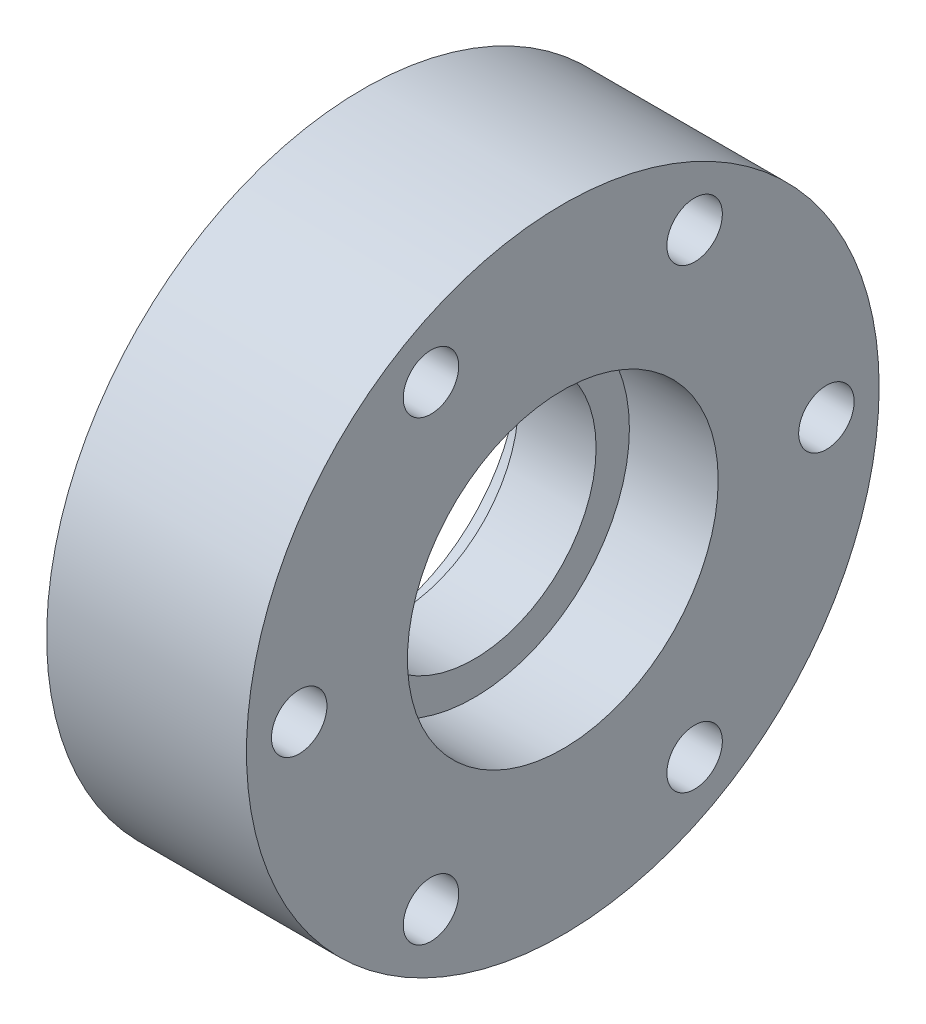
SolidWorks part; units mm, degrees
ref_plane "Front Plane" through (0, 0, 0) normal (0, 0, 1) x (1, 0, 0)
ref_plane "Top Plane" through (0, 0, 0) normal (0, 1, 0) x (1, 0, 0)
ref_plane "Right Plane" through (0, 0, 0) normal (1, 0, 0) x (0, 0, -1)
sketch "Sketch1" plane through (0, 0, 0) normal (1, 0, 0) x (0, 0, -1)
  line L0 (-23.75, 0) -> (0, 0) construction
  circle A0 centre (0, 0) radius 28.5
  circle A1 centre (0, 0) radius 11
  circle A2 centre (-23.75, 0) radius 2.5
  circle A3 centre (-11.875, 20.5681) radius 2.5
  circle A4 centre (11.875, 20.5681) radius 2.5
  circle A5 centre (23.75, 0) radius 2.5
  circle A6 centre (11.875, -20.5681) radius 2.5
  circle A7 centre (-11.875, -20.5681) radius 2.5
  point P18 (0, 0)
  dimension "D2" = 5
  dimension "D3" = 57
  dimension "D4" = 22
  dimension "D1" = 23.75
  dimension "D5" = 6
extrude "Boss-Extrude1" add sketch "Sketch1" along normal blind 18
sketch "Sketch2" plane through (18, 0, 0) normal (1, 0, 0) x (0, 0, -1)
  circle A1 centre (0, 0) radius 14
  circle A2 centre (0, 0) radius 11 construction
  circle A3 centre (0, 0) radius 11
  dimension "D1" = 28
extrude "Cut-Extrude1" cut sketch "Sketch2" against normal blind 8
sketch "Sketch3" plane through (0, 0, 0) normal (-1, 0, 0) x (0, 0, 1)
  circle A0 centre (0, 0) radius 14 construction
  circle A1 centre (0, 0) radius 14
  circle A2 centre (0, 0) radius 11 construction
  circle A3 centre (0, 0) radius 11
extrude "Cut-Extrude2" cut sketch "Sketch3" against normal blind 3
